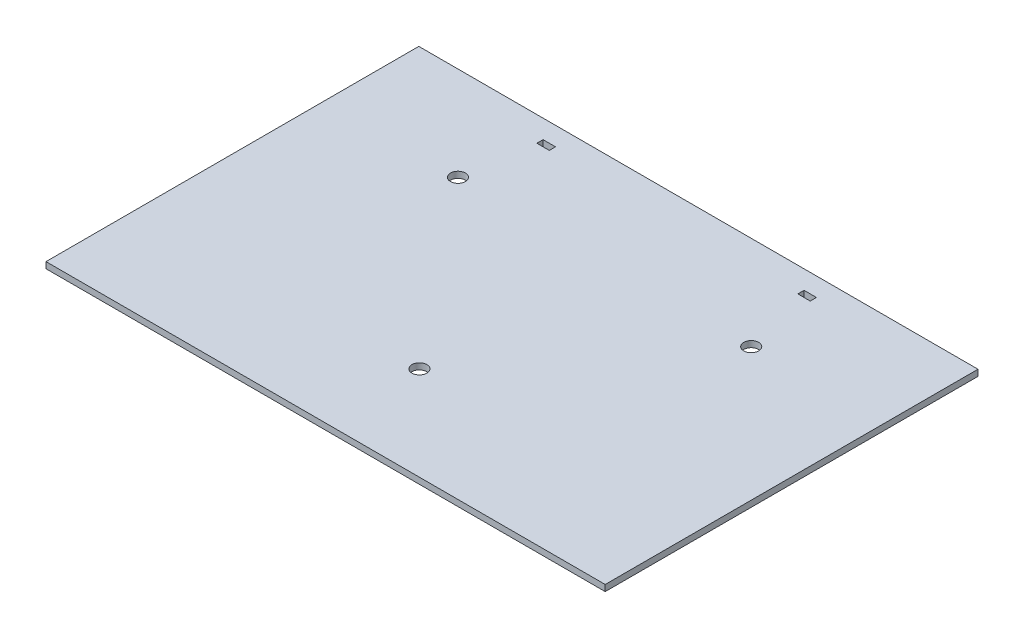
SolidWorks part; units mm, degrees
ref_plane "Front Plane" through (0, 0, 0) normal (0, 0, 1) x (1, 0, 0)
ref_plane "Top Plane" through (0, 0, 0) normal (0, 1, 0) x (1, 0, 0)
ref_plane "Right Plane" through (0, 0, 0) normal (1, 0, 0) x (0, 0, -1)
sketch "Sketch1" plane through (0, 0, 0) normal (0, 1, 0) x (1, 0, 0)
  line L1 (-225, -150) -> (225, -150)
  line L2 (-225, -150) -> (-225, 150)
  line L3 (-225, 150) -> (225, 150)
  line L4 (225, -150) -> (225, 150)
  line L5 (-225, -150) -> (225, 150) construction
  line L6 (-225, 150) -> (225, -150) construction
  point P0 (0, 0)
  dimension "D1" = 450
  dimension "D2" = 300
extrude "Extrude1" add sketch "Sketch1" against normal blind 5
sketch "Sketch2" plane through (0, 0, 0) normal (0, 1, 0) x (1, 0, 0)
  line L0 (0, -74.5) -> (0, 74.5) construction
  line L1 (-118, 74.5) -> (118, 74.5) construction
  circle A0 centre (0, -74.5) radius 6
  circle A1 centre (118, 74.5) radius 6
  circle A2 centre (-118, 74.5) radius 6
  dimension "D1" = 12
  dimension "D2" = 236
  dimension "D3" = 149
extrude "Extrude2" cut sketch "Sketch2" against normal up to next
sketch "Sketch3" plane through (0, 0, 0) normal (0, 1, 0) x (1, 0, 0)
  line L0 (-225, 150) -> (-225, -150) construction
  line L1 (210, -135) -> (-210, -135) construction
  line L2 (210, -135) -> (210, 135) construction
  line L3 (210, 135) -> (-210, 135) construction
  line L4 (-210, -135) -> (-210, 135) construction
  line L5 (210, -135) -> (-210, 135) construction
  line L6 (210, 135) -> (-210, -135) construction
  line L7 (225, 150) -> (-225, 150) construction
  line L8 (0, -135) -> (0, 135) construction
  line L9 (-110, 135) -> (-100, 135)
  line L10 (-110, 135) -> (-110, 130)
  line L11 (-110, 130) -> (-100, 130)
  line L12 (-100, 135) -> (-100, 130)
  line L13 (100, 135) -> (110, 135)
  line L14 (100, 135) -> (100, 130)
  line L15 (100, 130) -> (110, 130)
  line L16 (110, 135) -> (110, 130)
  line L17 (-210, 0) -> (210, 0) construction
  point P0 (0, 0)
  dimension "D1" = 15
  dimension "D2" = 15
  dimension "D3" = 5
  dimension "D4" = 10
  dimension "D5" = 200
extrude "Extrude3" cut sketch "Sketch3" against normal up to next
